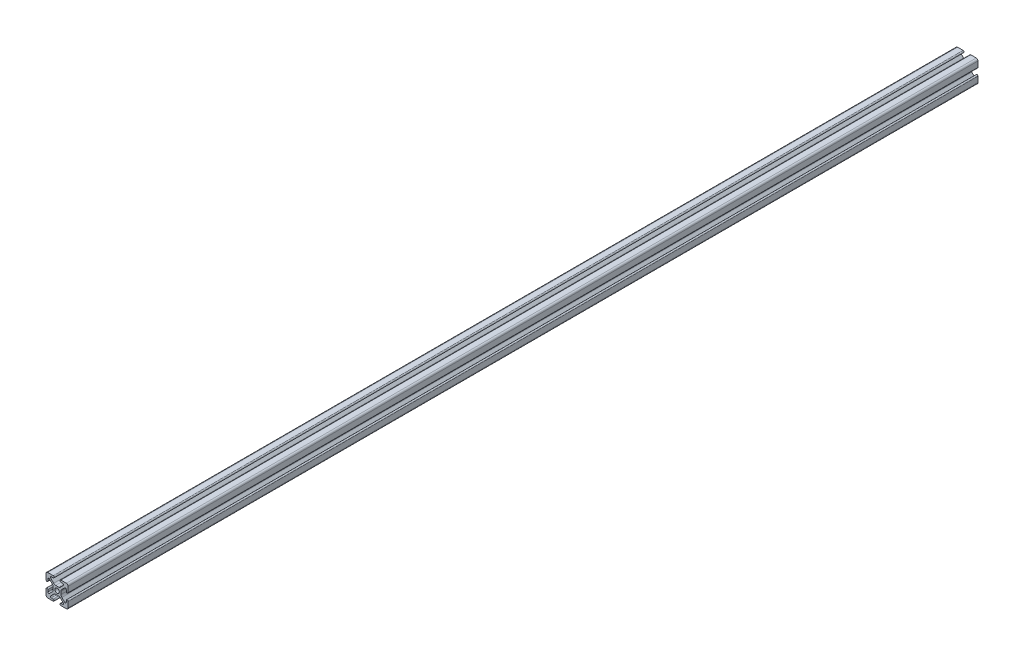
SolidWorks part; units mm, degrees
material "6061 Alloy"
ref_plane "Front Plane" through (0, 0, 0) normal (0, 0, 1) x (1, 0, 0)
ref_plane "Top Plane" through (0, 0, 0) normal (0, 1, 0) x (1, 0, 0)
ref_plane "Right Plane" through (0, 0, 0) normal (1, 0, 0) x (0, 0, -1)
sketch "Sketch1" plane through (0, 0, 0) normal (0, 0, 1) x (1, 0, 0)
  line L0 (-8.6363, 7.1116) -> (-5.4322, 3.9121)
  line L1 (-4.455, 1.5554) -> (-4.455, -1.5554)
  line L2 (-5.4322, -3.9121) -> (-8.6363, -7.1116)
  line L3 (-10.36, -6.3969) -> (-10.36, -4.32)
  line L4 (-12.5, -4.32) -> (-12.5, -8.6518)
  line L5 (-12.5, -8.6518) -> (-12.5, -10.5371)
  line L6 (-10.5371, -12.5) -> (-8.4416, -12.5)
  line L7 (-8.4416, -12.5) -> (-4.3879, -12.5)
  line L8 (-4.3879, -10.36) -> (-6.42, -10.36)
  line L9 (-7.1337, -8.6353) -> (-3.7953, -5.3018)
  line L10 (-1.5554, -4.375) -> (1.5554, -4.375)
  line L11 (10.36, 4.32) -> (10.36, 6.3969)
  line L12 (12.5, 7.9913) -> (12.5, 4.32)
  line L13 (12.5, 10.5371) -> (12.5, 7.9913)
  line L14 (4.32, 12.5) -> (10.5371, 12.5)
  line L16 (6.42, 10.36) -> (4.32, 10.36)
  line L17 (3.7953, 5.3018) -> (7.1337, 8.6353)
  line L18 (7.1337, -8.6353) -> (3.7953, -5.3018)
  line L19 (4.3879, -10.36) -> (6.42, -10.36)
  line L20 (8.4416, -12.5) -> (4.3879, -12.5)
  line L21 (10.5371, -12.5) -> (8.4416, -12.5)
  line L22 (12.5, -8.6518) -> (12.5, -10.5371)
  line L23 (12.5, -4.32) -> (12.5, -8.6518)
  line L24 (10.36, -6.3969) -> (10.36, -4.32)
  line L25 (5.4322, -3.9121) -> (8.6363, -7.1116)
  line L26 (4.455, 1.5554) -> (4.455, -1.5554)
  line L27 (8.6363, 7.1116) -> (5.4322, 3.9121)
  line L28 (1.5554, 4.375) -> (-1.5554, 4.375)
  line L29 (-3.7953, 5.3018) -> (-7.1337, 8.6353)
  line L30 (-6.42, 10.36) -> (-4.32, 10.36)
  line L32 (-4.32, 12.5) -> (-10.5371, 12.5)
  line L33 (-12.5, 10.5371) -> (-12.5, 7.9913)
  line L34 (-12.5, 7.9913) -> (-12.5, 4.32)
  line L35 (-10.36, 4.32) -> (-10.36, 6.3969)
  line L36 (-15.7693, 0) -> (12.5, 0) construction
  line L37 (0, 13.9334) -> (0, -12.3541) construction
  circle A0 centre (0, 0) radius 2.5
  arc A1 (-8.6363, 7.1116) -> (-10.36, 6.3969) centre (-9.35, 6.3969) ccw
  arc A2 (-4.455, 1.5554) -> (-5.4322, 3.9121) centre (-7.7855, 1.5554) ccw
  arc A3 (-5.4322, -3.9121) -> (-4.455, -1.5554) centre (-7.7855, -1.5554) ccw
  arc A4 (-10.36, -6.3969) -> (-8.6363, -7.1116) centre (-9.35, -6.3969) ccw
  arc A5 (-10.36, -4.32) -> (-12.5, -4.32) centre (-11.43, -4.32) ccw
  arc A6 (-12.5, -10.5371) -> (-10.5371, -12.5) centre (-10.5371, -10.5371) ccw
  arc A7 (-4.3879, -12.5) -> (-4.3879, -10.36) centre (-4.3879, -11.43) ccw
  arc A8 (-7.1337, -8.6353) -> (-6.42, -10.36) centre (-6.42, -9.35) ccw
  arc A9 (-1.5554, -4.375) -> (-3.7953, -5.3018) centre (-1.5554, -7.545) ccw
  arc A10 (12.5, 4.32) -> (10.36, 4.32) centre (11.43, 4.32) cw
  arc A11 (10.5371, 12.5) -> (12.5, 10.5371) centre (10.5371, 10.5371) cw
  arc A12 (4.32, 10.36) -> (4.32, 12.5) centre (4.32, 11.43) cw
  arc A13 (6.42, 10.36) -> (7.1337, 8.6353) centre (6.42, 9.35) cw
  arc A14 (3.7953, 5.3018) -> (1.5554, 4.375) centre (1.5554, 7.545) cw
  arc A15 (1.5554, -4.375) -> (3.7953, -5.3018) centre (1.5554, -7.545) cw
  arc A16 (7.1337, -8.6353) -> (6.42, -10.36) centre (6.42, -9.35) cw
  arc A17 (4.3879, -12.5) -> (4.3879, -10.36) centre (4.3879, -11.43) cw
  arc A18 (12.5, -10.5371) -> (10.5371, -12.5) centre (10.5371, -10.5371) cw
  arc A19 (10.36, -4.32) -> (12.5, -4.32) centre (11.43, -4.32) cw
  arc A20 (10.36, -6.3969) -> (8.6363, -7.1116) centre (9.35, -6.3969) cw
  arc A21 (5.4322, -3.9121) -> (4.455, -1.5554) centre (7.7855, -1.5554) cw
  arc A22 (4.455, 1.5554) -> (5.4322, 3.9121) centre (7.7855, 1.5554) cw
  arc A23 (8.6363, 7.1116) -> (10.36, 6.3969) centre (9.35, 6.3969) cw
  arc A24 (-3.7953, 5.3018) -> (-1.5554, 4.375) centre (-1.5554, 7.545) ccw
  arc A25 (-6.42, 10.36) -> (-7.1337, 8.6353) centre (-6.42, 9.35) ccw
  arc A26 (-4.32, 10.36) -> (-4.32, 12.5) centre (-4.32, 11.43) ccw
  arc A27 (-10.5371, 12.5) -> (-12.5, 10.5371) centre (-10.5371, 10.5371) ccw
  arc A28 (-12.5, 4.32) -> (-10.36, 4.32) centre (-11.43, 4.32) ccw
  dimension "D4" = 14.86
  dimension "D5" = 2.14
  dimension "D6" = 6.5
  dimension "D7" = 8.75
  dimension "D8" = 1.01
  dimension "D9" = 3.17
  dimension "D14" = 5
  dimension "D1" = 25
  dimension "D2" = 8.91
  dimension "D3" = 12.5
  dimension "D12" = 2.14
extrude "Extrude1" add sketch "Sketch1" against normal blind 1027
